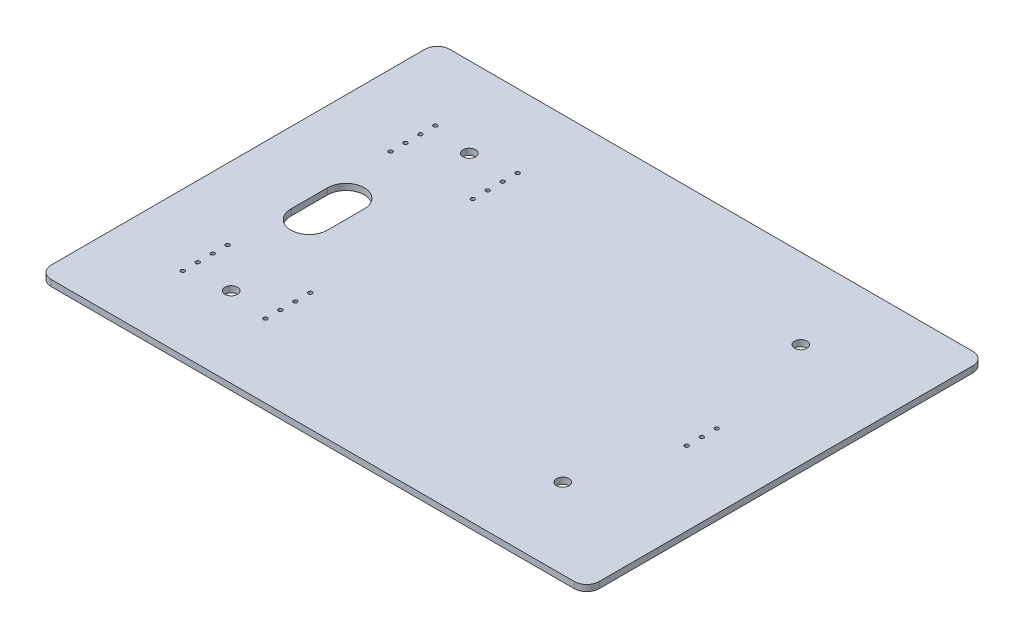
SolidWorks part; units mm, degrees
material "A-Glass Fiber"
ref_plane "Front Plane" through (0, 0, 0) normal (0, 0, 1) x (1, 0, 0)
ref_plane "Top Plane" through (0, 0, 0) normal (0, 1, 0) x (1, 0, 0)
ref_plane "Right Plane" through (0, 0, 0) normal (1, 0, 0) x (0, 0, -1)
sketch "Sketch1" plane through (0, 0, 0) normal (0, 1, 0) x (1, 0, 0)
  line L0 (0, 0) -> (70.284, 0) construction
  line L1 (-69.416, -50.8) -> (70.284, -50.8)
  line L2 (-69.416, -50.8) -> (-69.416, 50.8)
  line L3 (-69.416, 50.8) -> (70.284, 50.8)
  line L4 (70.284, -50.8) -> (70.284, 50.8)
  line L5 (-69.416, -50.8) -> (70.284, 50.8) construction
  line L6 (-69.416, 50.8) -> (70.284, -50.8) construction
  line L7 (-65.3901, 45.3898) -> (-69.416, 45.3898) construction
  line L9 (66.2581, 45.3898) -> (70.284, 45.3898) construction
  point P0 (0.434, 0)
  point P12 (-36.8782, 45.665)
  point P13 (78.9581, 45.3898)
  point P15 (-52.6901, 45.3898)
  dimension "D1" = 101.6
  dimension "D2" = 139.7
extrude "Boss-Extrude1" add sketch "Sketch1" against normal blind 1.5875
sketch "Sketch2" plane through (0, 0, 0) normal (0, 1, 0) x (1, 0, 0)
  circle A1 centre (-51.2255, 24.505) radius 0.5
  circle A2 centre (-51.2255, 24.505) radius 0.5
  circle A3 centre (-30.2705, 28.315) radius 0.5
  circle A4 centre (-30.2705, 28.315) radius 0.5
  circle A5 centre (-30.2705, 32.125) radius 0.5
  circle A6 centre (-30.2705, 32.125) radius 0.5
  circle A7 centre (-30.2704, -32.135) radius 0.5
  circle A8 centre (-30.2704, -32.135) radius 0.5
  circle A9 centre (-30.2704, -28.325) radius 0.5
  circle A10 centre (-30.2704, -28.325) radius 0.5
  circle A11 centre (-30.2704, -24.515) radius 0.5
  circle A12 centre (-30.2704, -24.515) radius 0.5
  circle A13 centre (-30.2705, -20.705) radius 0.5
  circle A14 centre (-30.2705, -20.705) radius 0.5
  circle A15 centre (51.4795, -6.483) radius 0.5
  circle A16 centre (51.4795, -6.483) radius 0.5
  circle A17 centre (51.4795, -2.673) radius 0.5
  circle A18 centre (51.4795, -2.673) radius 0.5
  circle A19 centre (-51.2255, 28.315) radius 0.5
  circle A20 centre (-51.2255, 28.315) radius 0.5
  circle A21 centre (-51.2255, 32.125) radius 0.5
  circle A22 centre (-51.2255, 32.125) radius 0.5
  circle A23 centre (-51.3524, -32.135) radius 0.5
  circle A24 centre (-51.3524, -32.135) radius 0.5
  circle A25 centre (-51.3524, -28.325) radius 0.5
  circle A26 centre (-51.3524, -28.325) radius 0.5
  circle A27 centre (-51.3524, -24.515) radius 0.5
  circle A28 centre (-51.3524, -24.515) radius 0.5
  circle A29 centre (-51.3524, -20.705) radius 0.5
  circle A30 centre (-51.3524, -20.705) radius 0.5
  circle A31 centre (-30.2705, 20.695) radius 0.5
  circle A32 centre (-30.2705, 20.695) radius 0.5
  circle A33 centre (-30.2705, 24.505) radius 0.5
  circle A34 centre (-30.2705, 24.505) radius 0.5
  circle A35 centre (-40.7894, -30.35) radius 1.5875
  circle A36 centre (-40.7894, -30.35) radius 1.5875
  circle A37 centre (-40.7894, 30.35) radius 1.5875
  circle A38 centre (-40.7894, 30.35) radius 1.5875
  circle A39 centre (43.7106, 30.35) radius 1.5875
  circle A40 centre (43.7106, 30.35) radius 1.5875
  circle A41 centre (43.7106, -30.35) radius 1.5875
  circle A42 centre (43.7106, -30.35) radius 1.5875
  circle A43 centre (51.4795, 1.137) radius 0.5
  circle A44 centre (51.4795, 1.137) radius 0.5
  circle A45 centre (-51.2255, 20.695) radius 0.5
  circle A46 centre (-51.2255, 20.695) radius 0.5
  dimension "D10" = 0
  dimension "D11" = 0
  dimension "D12" = 0
  dimension "D13" = 0
  dimension "D14" = 0
  dimension "D15" = 0
  dimension "D16" = 0
  dimension "D17" = 0
  dimension "D18" = 0
  dimension "D19" = 0
  dimension "D20" = 0
  dimension "D21" = 0
  dimension "D22" = 0
  dimension "D23" = 0
  dimension "D24" = 0
  dimension "D25" = 0
  dimension "D26" = 0
  dimension "D27" = 0
  dimension "D28" = 0
  dimension "D29" = 0
  dimension "D30" = 0
  dimension "D31" = 0
  dimension "D32" = 0
extrude "Cut-Extrude1" cut sketch "Sketch2" against normal through all
sketch "Sketch3" plane through (0, 0, 0) normal (0, 1, 0) x (1, 0, 0)
  line L5 (-46.5829, 4.69) -> (-46.5829, -4.69) construction
  line L6 (-41.9129, 4.69) -> (-41.9129, -4.69)
  line L7 (-51.2529, 4.69) -> (-51.2529, -4.69)
  line L17 (-43.1829, 3.75) -> (-41.9129, 3.75) construction
  line L18 (-44.8329, 7.605) -> (-44.1792, 8.6939) construction
  line L19 (-46.5829, 7.605) -> (-46.5829, 9.36) construction
  line L20 (-44.8329, 7.605) -> (-48.3329, 7.605) construction
  line L21 (-46.5829, -7.605) -> (-46.5829, -9.36) construction
  line L22 (-48.3329, -7.605) -> (-44.8329, -7.605) construction
  arc A13 (-41.9129, 4.69) -> (-51.2529, 4.69) centre (-46.5829, 4.69) ccw
  arc A14 (-51.2529, -4.69) -> (-41.9129, -4.69) centre (-46.5829, -4.69) ccw
  arc A17 (-44.8329, 0.835) -> (-44.8329, 6.665) centre (-46.5829, 3.75) ccw construction
  point P2 (-46.5829, 0)
  dimension "D1" = 1.27
extrude "Cut-Extrude2" cut sketch "Sketch3" against normal through all
fillet "Fillet1" radius 3.175 4 edges at (-69.416, -0.7937, -50.8) (70.284, -0.7937, -50.8) (70.284, -0.7937, 50.8) (-69.416, -0.7937, 50.8)
sketch "Sketch4" plane through (0, -1.5875, 0) normal (0, -1, 0) x (1, 0, 0)
  line L4 (-34.2894, -10.598) -> (-39.2094, -10.598)
  line L5 (-34.2894, -25.33) -> (-34.2894, -10.598)
  line L6 (-39.2094, -25.33) -> (-34.2894, -25.33)
  line L7 (-39.2094, -10.598) -> (-39.2094, -25.33)
  line L8 (-34.2894, -10.598) -> (-39.2094, -10.598)
  line L9 (-34.2894, -25.33) -> (-34.2894, -10.598)
  line L10 (-39.2094, -25.33) -> (-34.2894, -25.33)
  line L11 (-39.2094, -10.598) -> (-39.2094, -25.33)
  line L12 (-34.2894, 25.33) -> (-39.2094, 25.33)
  line L13 (-34.2894, 10.598) -> (-34.2894, 25.33)
  line L14 (-39.2094, 10.598) -> (-34.2894, 10.598)
  line L15 (-39.2094, 25.33) -> (-39.2094, 10.598)
  line L16 (-34.2894, 25.33) -> (-39.2094, 25.33)
  line L17 (-34.2894, 10.598) -> (-34.2894, 25.33)
  line L18 (-39.2094, 10.598) -> (-34.2894, 10.598)
  line L19 (-39.2094, 25.33) -> (-39.2094, 10.598)
  line L20 (-44.3594, 10.598) -> (-39.4395, 10.598)
  line L21 (-39.4395, 10.598) -> (-39.4395, 25.33)
  line L22 (-39.4395, 25.33) -> (-44.3594, 25.33)
  line L23 (-44.3594, 25.33) -> (-44.3594, 10.598)
  line L24 (-44.3594, 10.598) -> (-39.4395, 10.598)
  line L25 (-39.4395, 10.598) -> (-39.4395, 25.33)
  line L26 (-39.4395, 25.33) -> (-44.3594, 25.33)
  line L27 (-44.3594, 25.33) -> (-44.3594, 10.598)
  line L28 (-39.4395, -10.598) -> (-44.3594, -10.598)
  line L29 (-39.4395, -25.33) -> (-39.4395, -10.598)
  line L30 (-44.3594, -25.33) -> (-39.4395, -25.33)
  line L31 (-44.3594, -10.598) -> (-44.3594, -25.33)
  line L32 (-39.4395, -10.598) -> (-44.3594, -10.598)
  line L33 (-39.4395, -25.33) -> (-39.4395, -10.598)
  line L34 (-44.3594, -25.33) -> (-39.4395, -25.33)
  line L35 (-44.3594, -10.598) -> (-44.3594, -25.33)
  line L36 (35.3095, 12.548) -> (40.2295, 12.548)
  line L37 (35.3095, 27.28) -> (35.3095, 12.548)
  line L38 (40.2295, 27.28) -> (35.3095, 27.28)
  line L39 (40.2295, 12.548) -> (40.2295, 27.28)
  line L40 (35.3095, 12.548) -> (40.2295, 12.548)
  line L41 (35.3095, 27.28) -> (35.3095, 12.548)
  line L42 (40.2295, 27.28) -> (35.3095, 27.28)
  line L43 (40.2295, 12.548) -> (40.2295, 27.28)
  dimension "D1" = 0
  dimension "D2" = 0
  dimension "D3" = 0
  dimension "D4" = 0
  dimension "D5" = 0
equation "\"62.5mi\"=0.1"
